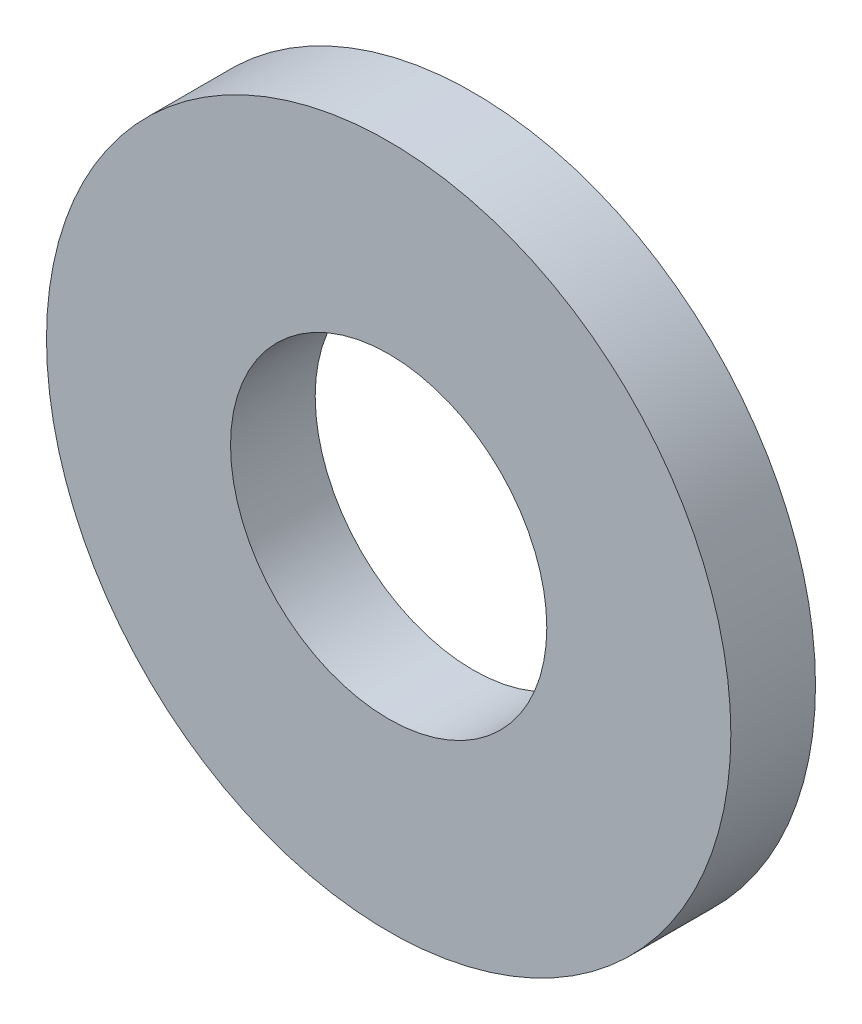
SolidWorks part; units mm, degrees
ref_plane "Front Plane" through (0, 0, 0) normal (0, 0, 1) x (1, 0, 0)
ref_plane "Top Plane" through (0, 0, 0) normal (0, 1, 0) x (1, 0, 0)
ref_plane "Right Plane" through (0, 0, 0) normal (1, 0, 0) x (0, 0, -1)
sketch "Sketch1" plane through (0, 0, 0) normal (0, 0, 1) x (1, 0, 0)
  circle A0 centre (0, 0) radius 10.9125
  circle A1 centre (0, 0) radius 23.6125
  dimension "D1" = 12.7
  dimension "D2" = 21.8249
extrude "Boss-Extrude1" add sketch "Sketch1" along normal blind 5.842
